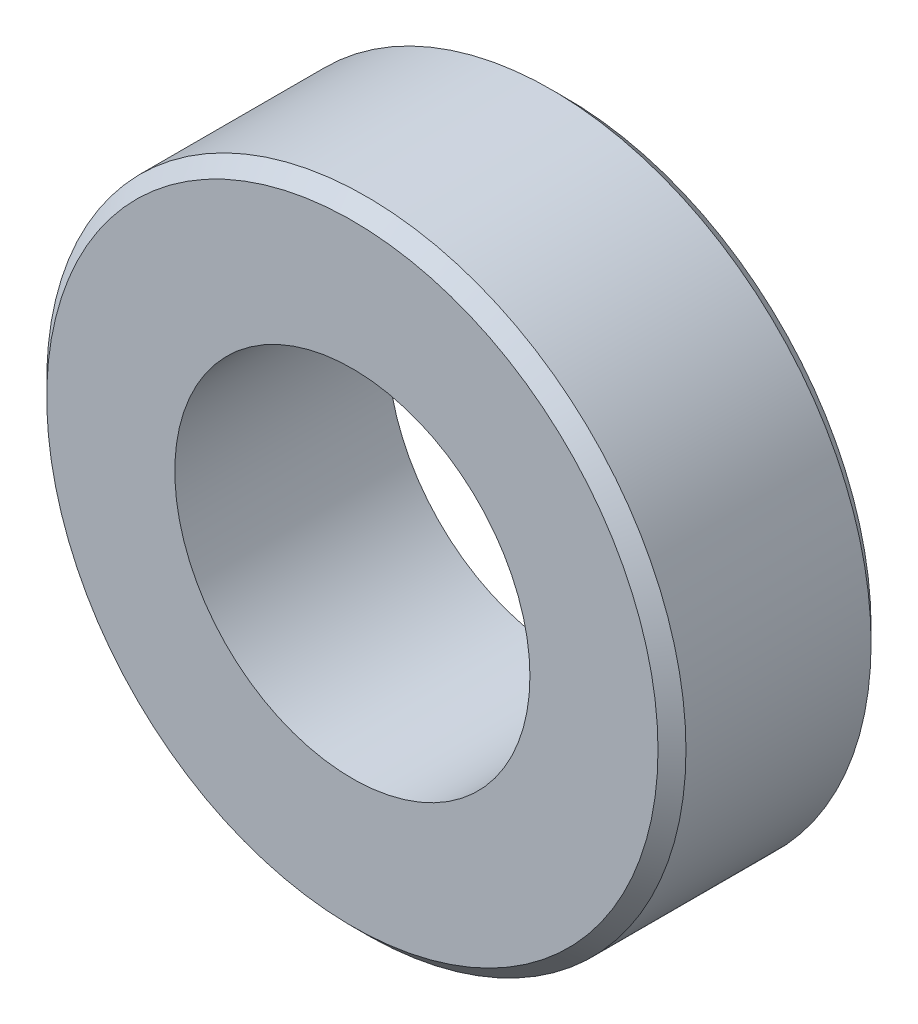
SolidWorks part; units mm, degrees
ref_plane "Front Plane" through (0, 0, 0) normal (0, 0, 1) x (1, 0, 0)
ref_plane "Top Plane" through (0, 0, 0) normal (0, 1, 0) x (1, 0, 0)
ref_plane "Right Plane" through (0, 0, 0) normal (1, 0, 0) x (0, 0, -1)
sketch "Sketch1" plane through (0, 0, 0) normal (0, 0, 1) x (1, 0, 0)
  circle A0 centre (0, 0) radius 11.43
  circle A1 centre (0, 0) radius 6.35
  dimension "D1" = 22.86
  dimension "D2" = 12.7
extrude "Boss-Extrude1" add sketch "Sketch1" along normal mid plane 7.62
chamfer "Chamfer1" distance 0.5 angle 45 2 edges at (11.43, 0, -3.81) (11.43, 0, 3.81)
